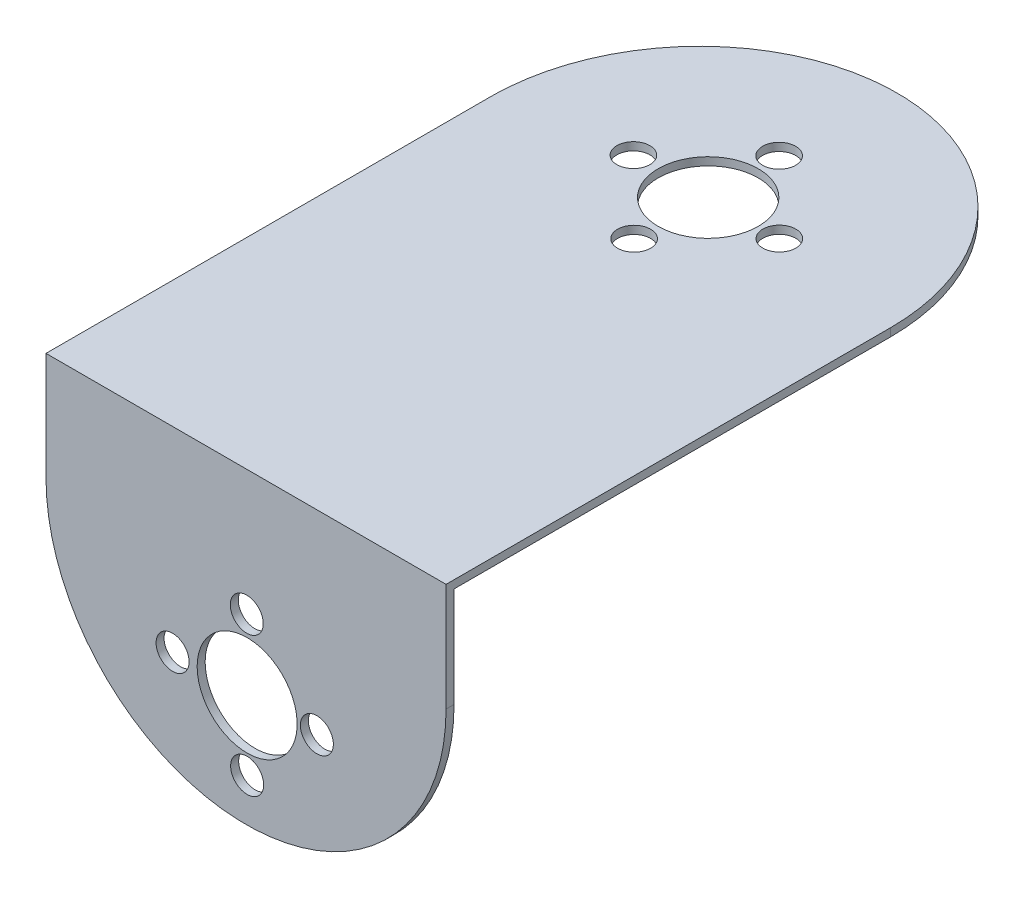
SolidWorks part; units mm, degrees
ref_plane "Front Plane" through (0, 0, 0) normal (0, 0, 1) x (1, 0, 0)
ref_plane "Top Plane" through (0, 0, 0) normal (0, 1, 0) x (1, 0, 0)
ref_plane "Right Plane" through (0, 0, 0) normal (1, 0, 0) x (0, 0, -1)
sketch "Sketch1" plane through (0, 0, 0) normal (0, 1, 0) x (1, 0, 0)
  line L1 (-49.9281, 0.853) -> (-9.9281, 0.853)
  line L2 (-49.9281, 0.853) -> (-49.9281, 60.853)
  line L3 (-49.9281, 60.853) -> (-9.9281, 60.853)
  line L4 (-9.9281, 0.853) -> (-9.9281, 60.853)
  dimension "D1" = 40
  dimension "D2" = 60
extrude "Boss-Extrude1" add sketch "Sketch1" along normal blind 0.8
sketch "Sketch2" plane through (0, 0.8, 0) normal (0, 1, 0) x (1, 0, 0)
  line L0 (-9.9281, 60.853) -> (-49.9281, 60.853) construction
  ellipse E0 centre (-29.9281, 60.853) end of major axis (-29.9281, 81.5258) minor radius 20
extrude "Boss-Extrude2" add sketch "Sketch2" against normal blind 0.8
sketch "Sketch5" plane through (0, 0.8, 0) normal (0, 1, 0) x (1, 0, 0)
  circle A0 centre (-30.3172, 63.0299) radius 0.5503
  circle A1 centre (-30.3172, 63.0299) radius 5
  circle A2 centre (-30.3859, 70.1928) radius 1.65
  circle A3 centre (-23.2059, 63.0299) radius 1.65
  circle A4 centre (-37.7264, 62.9612) radius 1.65
  circle A5 centre (-30.4546, 55.7581) radius 1.65
  dimension "D1" = 10
  dimension "D2" = 3.3
  dimension "D3" = 3.3
  dimension "D4" = 3.3
  dimension "D5" = 3.3
extrude "Cut-Extrude3" cut sketch "Sketch5" against normal blind 0.8 contours A5 | A3 | A4 | A2 | A1
sketch "Sketch6" plane through (0, 0, 0) normal (0, -1, 0) x (-1, 0, 0)
  line L0 (9.9281, 0.853) -> (9.9281, 60.853) construction
  line L1 (49.9281, 0.853) -> (9.9281, 0.853)
  line L2 (49.9281, 0.853) -> (49.9281, 16.4304)
  line L3 (49.9281, 16.4304) -> (9.9281, 16.4304)
  line L4 (9.9281, 0.853) -> (9.9281, 16.4304)
extrude "Cut-Extrude4" cut sketch "Sketch6" against normal blind 10
sketch "Sketch7" plane through (0, 0, 0) normal (0, -1, 0) x (-1, 0, 0)
  line L0 (9.9281, 16.4304) -> (9.9281, 60.853) construction
  line L1 (49.9281, 16.4304) -> (9.9281, 16.4304)
  line L2 (49.9281, 16.4304) -> (49.9281, 17.2304)
  line L3 (49.9281, 17.2304) -> (9.9281, 17.2304)
  line L4 (9.9281, 16.4304) -> (9.9281, 17.2304)
  dimension "D1" = 0.8
extrude "Boss-Extrude3" add sketch "Sketch7" along normal blind 10
sketch "Sketch8" plane through (0, 0, -17.2304) normal (0, 0, -1) x (-1, 0, 0)
  line L0 (49.9281, -10) -> (9.9281, -10) construction
  circle A0 centre (29.9281, -10) radius 20
extrude "Boss-Extrude4" add sketch "Sketch8" against normal blind 0.8 contours A0
sketch "Sketch9" plane through (0, 0, -17.2304) normal (0, 0, -1) x (-1, 0, 0)
  line L1 (13.0948, 0.8) -> (50.8146, 0.8)
  line L2 (13.0948, 0.8) -> (13.0948, 12.9366)
  line L3 (13.0948, 12.9366) -> (50.8146, 12.9366)
  line L4 (50.8146, 0.8) -> (50.8146, 12.9366)
extrude "Cut-Extrude5" cut sketch "Sketch9" against normal blind 0.8
sketch "Sketch10" plane through (0, 0, -17.2304) normal (0, 0, -1) x (-1, 0, 0)
  circle A0 centre (29.8162, -18.756) radius 5
  circle A1 centre (29.8535, -11.7486) radius 1.65
  circle A2 centre (37.271, -18.756) radius 1.65
  circle A3 centre (29.8162, -25.689) radius 1.65
  circle A4 centre (22.846, -18.6815) radius 1.65
  dimension "D1" = 10
  dimension "D2" = 3.3
  dimension "D3" = 3.3
  dimension "D4" = 3.3
  dimension "D5" = 3.3
extrude "Cut-Extrude8" cut sketch "Sketch10" against normal blind 9.8
